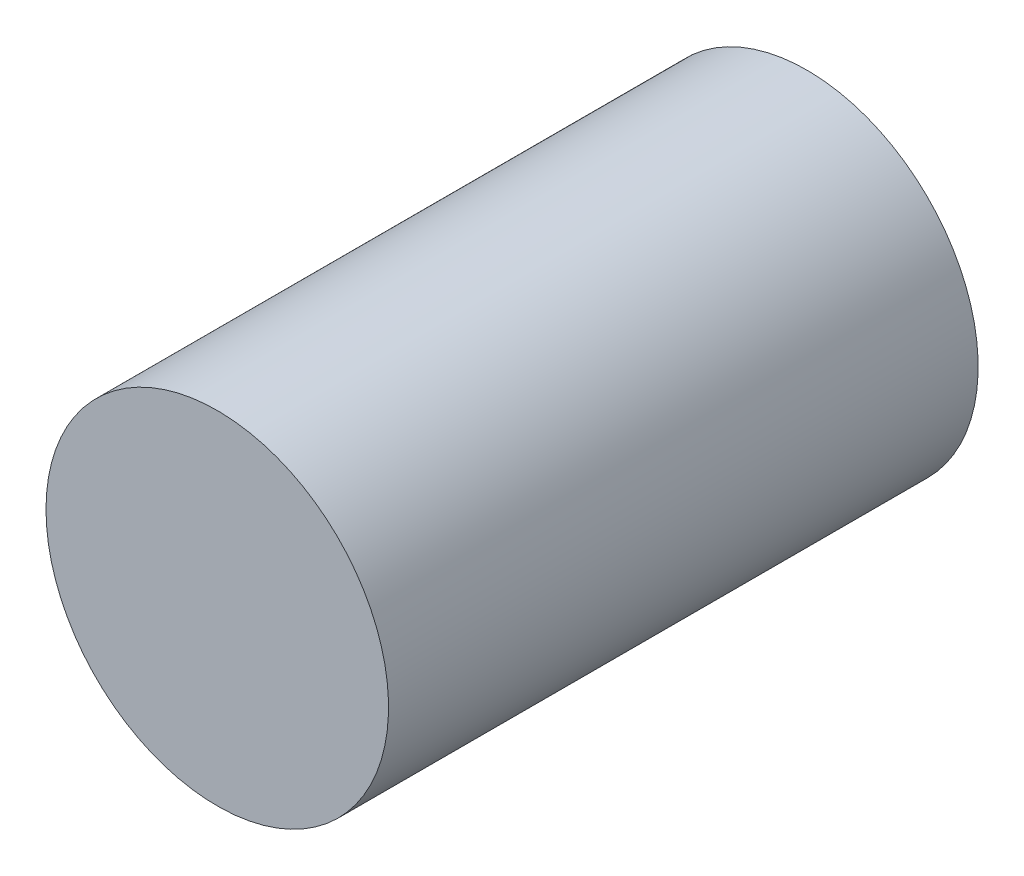
SolidWorks part; units mm, degrees
ref_plane "Front Plane" through (0, 0, 0) normal (0, 0, 1) x (1, 0, 0)
ref_plane "Top Plane" through (0, 0, 0) normal (0, 1, 0) x (1, 0, 0)
ref_plane "Right Plane" through (0, 0, 0) normal (1, 0, 0) x (0, 0, -1)
sketch "Sketch1" plane through (0, 0, 0) normal (0, 0, 1) x (1, 0, 0)
  circle A0 centre (0, 0) radius 6.1
extrude "Envelope" add sketch "Sketch1" along normal blind 21
